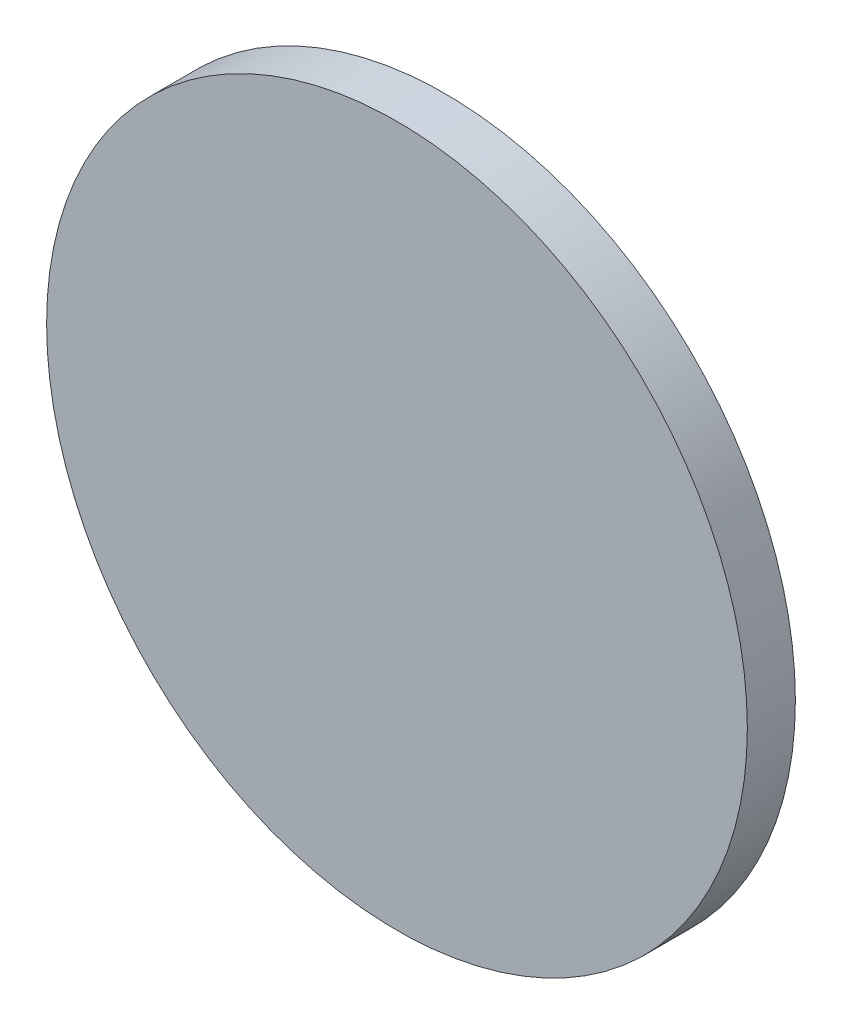
SolidWorks part; units mm, degrees
ref_plane "Front Plane" through (0, 0, 0) normal (0, 0, 1) x (1, 0, 0)
ref_plane "Top Plane" through (0, 0, 0) normal (0, 1, 0) x (1, 0, 0)
ref_plane "Right Plane" through (0, 0, 0) normal (1, 0, 0) x (0, 0, -1)
sketch "Sketch1" plane through (0, 0, 0) normal (0, 0, 1) x (1, 0, 0)
  circle A0 centre (0, 0) radius 17.5
  dimension "D1" = 35
extrude "Boss-Extrude1" add sketch "Sketch1" along normal blind 2.4
